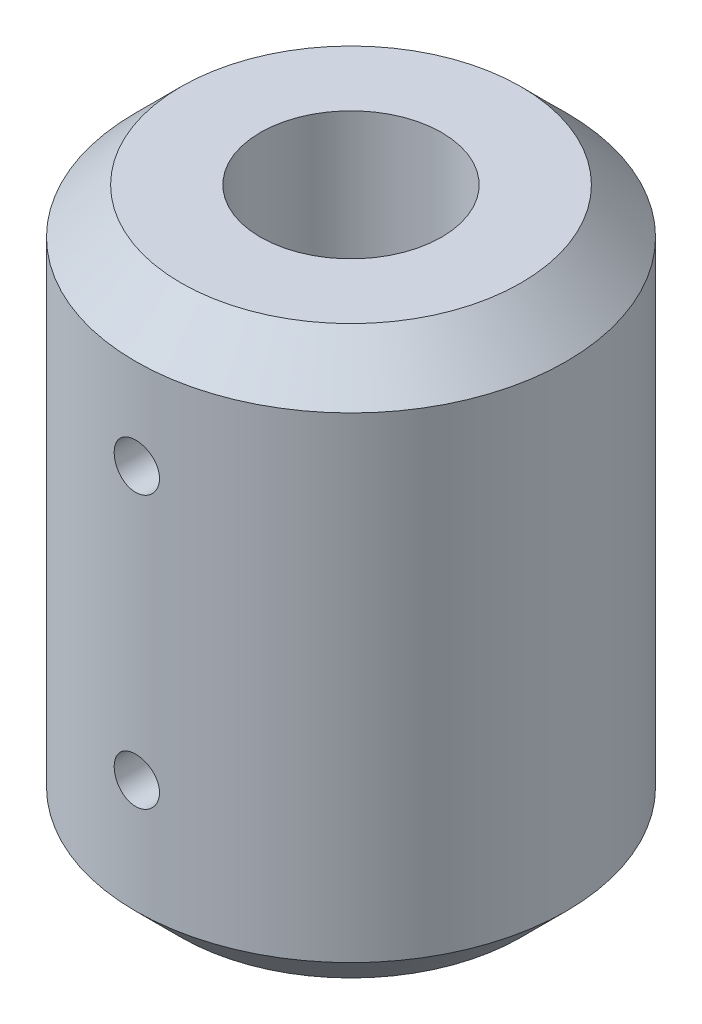
SolidWorks part; units mm, degrees
ref_plane "Front (XY)" through (0, 0, 0) normal (0, 0, 1) x (1, 0, 0)
ref_plane "Top (XZ)" through (0, 0, 0) normal (0, 1, 0) x (1, 0, 0)
ref_plane "Right (YZ)" through (0, 0, 0) normal (1, 0, 0) x (0, 0, -1)
sketch "Sketch1" plane through (0, 0, 0) normal (0, 1, 0) x (1, 0, 0)
  circle A0 centre (0, 0) radius 9.5
  dimension "D1" = 19
extrude "Boss-Extrude1" add sketch "Sketch1" along normal blind 25
sketch "Sketch2" plane through (0, 0, 0) normal (0, 1, 0) x (1, 0, 0)
  circle A0 centre (0, 0) radius 2.5
  dimension "D1" = 5
extrude "Cut-Extrude1" cut sketch "Sketch2" along normal blind 15
ref_plane "Plane1" through (0, 14.5, 0) normal (0, 1, 0) x (1, 0, 0)
sketch "Sketch3" plane through (0, 14.5, 0) normal (0, 1, 0) x (1, 0, 0)
  circle A0 centre (0, 0) radius 4
  dimension "D1" = 8
extrude "Cut-Extrude2" cut sketch "Sketch3" along normal through all
chamfer "Chamfer1" distance 2 angle 45 2 edges at (0, 0, 9.5) (0, 25, 9.5)
ref_plane "Plane2" through (0, 0, 9.5) normal (0, 0, 1) x (1, 0, 0)
sketch "Sketch13" plane through (0, 0, 9.5) normal (0, 0, 1) x (1, 0, 0)
  line L0 (0, 0) -> (0, 25) construction
  line L1 (7.5, 25) -> (-7.5, 25) construction
  circle A0 centre (0, 19) radius 1
  circle A1 centre (0, 7) radius 1
  dimension "D1" = 2
  dimension "D2" = 12
  dimension "D3" = 7
extrude "Cut-Extrude3" cut sketch "Sketch13" against normal up to next
